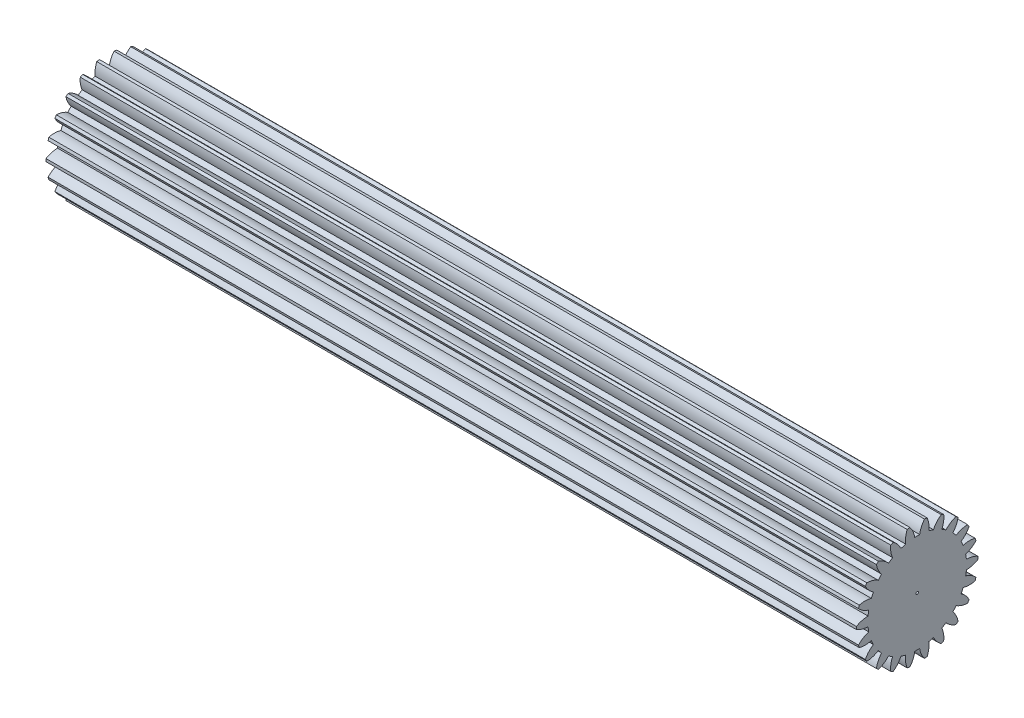
SolidWorks part; units mm, degrees
ref_plane "Plane1" through (0, 0, 0) normal (0, 0, 1) x (1, 0, 0)
ref_plane "Plane2" through (0, 0, 0) normal (0, 1, 0) x (1, 0, 0)
ref_plane "Plane3" through (0, 0, 0) normal (1, 0, 0) x (0, 0, -1)
sketch "HoldingSke" plane through (0, 0, 0) normal (0, 1, 0) x (1, 0, 0)
  line L0 (0, 0) -> (376.8075, -152.2401)
  line L1 (-15, 0) -> (100, 0) construction
  line L2 (0, 0) -> (-2.1039, 2.3779)
  line L3 (0, 0) -> (-11.863, 4.5341)
  line L4 (0, 0) -> (8.0072, 3.2351)
  line L5 (0, 0) -> (-47.5972, -17.7524)
  line L6 (0, 0) -> (-210.5566, -142.0631)
  line L7 (-2.1039, 2.3779) -> (52.5694, 250.4239)
  line L8 (-76.2, 54.61) -> (-75.184, 54.61)
  line L9 (-71.009, 38.7566) -> (-53.1078, 45.2721)
  line L10 (-76.2, 71.12) -> (104.1128, 71.12)
  line L11 (0, 0) -> (-254, 0)
  line L12 (-76.2, 101.6) -> (-76.1428, 101.6)
  line L13 (24.9733, 27.94) -> (52.9518, 28.4284)
  line L14 (24.9733, 27.94) -> (24.9746, 27.94)
  line L15 (24.9733, 27.94) -> (100.4006, 29.5858)
  circle A0 centre (0, 0) radius 0.3969
  circle A1 centre (0, 0) radius 15.4769
  circle A2 centre (0, 0) radius 38.1
  circle A3 centre (0, 0) radius 0.3969
  dimension "MHD" = 30.9537
  dimension "Hub_dia" = 76.2
  dimension "Bore" = 0.7937
  dimension "MBD" = 0.7937
  dimension "Num_teeth" = 22
  dimension "Pitch" = 406.4
  dimension "Overall_len" = 50.8
  dimension "Show_teeth" = 22
  dimension "Thickness" = 254
  dimension "OAL" = 254.0001
  dimension "T_dim" = 1.016
  dimension "Ap" = 20
  dimension "H" = 19.05
  dimension "Pitch_radius" = 180.3128
  dimension "Width" = 254
  dimension "Backlash" = 0.0571
  dimension "Addendum_fac" = 1
  dimension "Dedendum_fac" = 1.25
  dimension "Clearance_fac" = 0.25
  dimension "Dedendum_add" = 0.0013
sketch "BasProSke" plane through (0, 0, 0) normal (0, 1, 0) x (1, 0, 0)
  line L0 (-10, 0) -> (60, 0) construction
  line L1 (0, 0) -> (0, 19.05)
  line L2 (0, 0) -> (254, 0)
  line L3 (254, 0) -> (254, 19.05)
  line L4 (254, 19.05) -> (0, 19.05)
  dimension "Thickness" = 254
  dimension "Diameter" = 38.1
revolve "Base-Revolve" add sketch "BasProSke" angle 360 about L0
sketch "TooCutSke" plane through (0, 0, 0) normal (1, 0, 0) x (0, 0, -1)
  line L1 (0, 0) -> (0, 107) construction
  line L2 (0, 0) -> (-1.3457, 17.4106) construction
  line L3 (0, 0) -> (-4.9596, 34.495) construction
  line L4 (-1.3457, 17.4106) -> (-2.4798, 17.2475) construction
  arc A0 (0.7746, 15.4575) -> (-0.7746, 15.4575) centre (0, 0) ccw
  arc A1 (2.3019, 18.936) -> (-2.3019, 18.936) centre (0, 0) ccw
  circle A2 centre (0, 0) radius 17.4625 construction
  circle A3 centre (0, 0) radius 16.4094 construction
  arc A4 (-0.7746, 15.4575) -> (-2.3019, 18.936) centre (-7.6929, 14.4944) ccw
  arc A5 (2.3019, 18.936) -> (0.7746, 15.4575) centre (7.6929, 14.4944) ccw
  dimension "Root_dia" = 30.9537
  dimension "Overcut_dia" = 38.1508
  dimension "Pitch_dia" = 34.925
  dimension "Base_dia" = 32.8188
  dimension "Flank_rad" = 6.985
  dimension "Half_ang" = 8.182
  dimension "Half_CT" = 1.1457
extrude "ToothCut" cut sketch "TooCutSke" along normal through all
fillet "Breaks" [suppressed] radius 0.0318
fillet "RootFillets" [suppressed] radius 0.3981
pattern_circular "TeethCuts" count 22 every 16.364 about axis through (-10, 0, 0) along (1, 0, 0) of "ToothCut", "RootFillets", "Breaks"
sketch "HubNeaOneSke" plane through (0, 0, 0) normal (-1, 0, 0) x (0, 0, 1)
  circle A0 centre (0, 0) radius 15.4769
  dimension "Diameter" = 30.9537
extrude "HubNearOne" [suppressed] add sketch "HubNeaOneSke" along normal blind 38.1001
sketch "HubNeaBotSke" plane through (0, 0, 0) normal (-1, 0, 0) x (0, 0, 1)
  circle A0 centre (0, 0) radius 15.4769
  dimension "Diameter" = 30.9537
extrude "HubNearBoth" [suppressed] add sketch "HubNeaBotSke" along normal blind 19.05
ref_plane "FarPln" through (254, 0, 0) normal (1, 0, 0) x (0, 0, -1)
sketch "HubFarSke" plane through (254, 0, 0) normal (1, 0, 0) x (0, 0, -1)
  circle A0 centre (0, 0) radius 15.4769
  dimension "Diameter" = 30.9537
extrude "HubFar" [suppressed] add sketch "HubFarSke" along normal blind 19.05
sketch "BorSke" plane through (0, 0, 0) normal (1, 0, 0) x (0, 0, -1)
  circle A0 centre (0, 0) radius 0.3969
  dimension "Diameter" = 0.7937
extrude "Bore" cut sketch "BorSke" along normal mid plane 508.0001
sketch "KeySke" plane through (0, 0, 0) normal (1, 0, 0) x (0, 0, -1)
  line L0 (-0.127, 0) -> (-0.127, 0.6191)
  line L1 (-0.127, 0.6191) -> (0.127, 0.6191)
  line L2 (0.127, 0.6191) -> (0.127, 0)
  line L3 (0, 0) -> (0, 34) construction
  line L4 (-0.127, 0) -> (0.127, 0)
  dimension "Offset" = 0.6191
  dimension "Width" = 0.254
extrude "Keyway" [suppressed] cut sketch "KeySke" along normal mid plane 508.0001
pattern_circular "Keyway2" [suppressed] count 2 every 90 about axis through (-10, 0, 0) along (1, 0, 0)
equation "' \"Pitch@HoldingSke\" = 4"
equation "' \"Num_teeth@HoldingSke\" = 12"
equation "' \"Ap@HoldingSke\" =  20"
equation "' \"Ap@HoldingSke\" = 20"
equation "' \"Width@HoldingSke\" = 0.5"
equation "' \"Hub_dia@HoldingSke\"= 1"
equation "' \"Hub_dia@HoldingSke\" = 1"
equation "' \"Overall_len@HoldingSke\" = 1.0"
equation "' \"Bore@HoldingSke\" = 0.75"
equation "' \"T_dim@HoldingSke\" = 0.85"
equation "' \"Width@KeySke\" = 0.25"
equation "' \"Show_teeth@HoldingSke\" = 13"
equation "' \"Backlash@HoldingSke\" = 0.009"
equation "' \"Addendum_fac@HoldingSke\" = 1.0"
equation "' \"Dedendum_fac@HoldingSke\" = 1.25"
equation "' \"Dedendum_add@HoldingSke\" = 0.00005"
equation "' \"Clearance_fac@HoldingSke\" = 0.25"
equation "' \"Pitch@HoldingSke\" = 0.5"
equation "' \"Num_teeth@HoldingSke\" = 23"
equation "' \"Show_teeth@HoldingSke\" = 23"
equation "' \"Backlash@HoldingSke\" = 0.0375"
equation "\"Overcut_dia@TooCutSke\" = (\"Num_teeth@HoldingSke\" + 2 * \"Addendum_fac@HoldingSke\") / \"Pitch@HoldingSke\" + 0.002"
equation "\"Pitch_dia@TooCutSke\" = \"Num_teeth@HoldingSke\" / \"Pitch@HoldingSke\""
equation "\"Base_dia@TooCutSke\" = \"Num_teeth@HoldingSke\" / \"Pitch@HoldingSke\" * cos((\"Ap@HoldingSke\"  * 3.14159265 / 180))"
equation "\"Root_dia@TooCutSke\" = (\"Num_teeth@HoldingSke\" + 2) / \"Pitch@HoldingSke\" - 2 * (\"Addendum_fac@HoldingSke\" + \"Dedendum_fac@HoldingSke\") / \"Pitch@HoldingSke\" - \"Dedendum_add@HoldingSke\" * 2"
equation "\"Half_ang@TooCutSke\" = 180 / \"Num_teeth@HoldingSke\""
equation "\"Half_CT@TooCutSke\" = \"Num_teeth@HoldingSke\" / \"Pitch@HoldingSke\" * sin((3.14159265 / 2 / \"Num_teeth@HoldingSke\")) / 2 - 7 * \"Backlash@HoldingSke\" / 4"
equation "\"Flank_rad@TooCutSke\" = \"Num_teeth@HoldingSke\" / \"Pitch@HoldingSke\" / 5"
equation "\"Radius@RootFillets\" = \"Clearance_fac@HoldingSke\" / \"Pitch@HoldingSke\" + \"Dedendum_add@HoldingSke\""
equation "\"Break_rad@Breaks\" = 0.02 / \"Pitch@HoldingSke\""
equation "\"Thickness@HoldingSke\" = \"Width@HoldingSke\""
equation "\"OAL@HoldingSke\" = \"Thickness@HoldingSke\""
equation "\"MHD@HoldingSke\" = (\"Num_teeth@HoldingSke\" + 2) / \"Pitch@HoldingSke\" - 2 * (\"Addendum_fac@HoldingSke\" + \"Dedendum_fac@HoldingSke\")  / \"Pitch@HoldingSke\" - \"Dedendum_add@HoldingSke\" * 2"
equation "\"MBD@HoldingSke\" = (\"Num_teeth@HoldingSke\" + 2) / \"Pitch@HoldingSke\" - 2 * (\"Addendum_fac@HoldingSke\" + \"Dedendum_fac@HoldingSke\")  / \"Pitch@HoldingSke\" - \"Dedendum_add@HoldingSke\" * 2 - 0.002"
equation "\"MHD@HoldingSke\" = ((sgn( \"MHD@HoldingSke\" - \"Hub_dia@HoldingSke\" )-1)*( \"MHD@HoldingSke\" - \"Hub_dia@HoldingSke\" ))/-2+ \"Hub_dia@HoldingSke\""
equation "\"MBD@HoldingSke\" = ((sgn( \"MBD@HoldingSke\" - \"Bore@HoldingSke\" )-1)*( \"MBD@HoldingSke\" - \"Bore@HoldingSke\" ))/-2+ \"Bore@HoldingSke\""
equation "\"OAL@HoldingSke\" = ((sgn( \"OAL@HoldingSke\" - \"Overall_len@HoldingSke\" )+1)*( \"OAL@HoldingSke\" - \"Overall_len@HoldingSke\" ))/2 + \"Overall_len@HoldingSke\" + 0.000002"
equation "\"Num_teeth@TeethCuts\" = int( \"Show_teeth@HoldingSke\" ) + 1"
equation "\"Num_teeth@TeethCuts\" = ((sgn( \"Num_teeth@TeethCuts\" - \"Num_teeth@HoldingSke\" )-1)*( \"Num_teeth@TeethCuts\" - \"Num_teeth@HoldingSke\" ))/-2+ \"Num_teeth@HoldingSke\""
equation "\"Num_teeth@TeethCuts\" = ((sgn( \"Num_teeth@TeethCuts\" - 2.0)+1)*( \"Num_teeth@TeethCuts\" - 2.0))/2 +2.0"
equation "\"Angle@TeethCuts\" = 360.0 / \"Num_teeth@HoldingSke\""
equation "\"Diameter@BasProSke\" = (\"Num_teeth@HoldingSke\" + 2 * \"Addendum_fac@HoldingSke\") / \"Pitch@HoldingSke\""
equation "\"Thickness@BasProSke\"  = \"Thickness@HoldingSke\""
equation "' \"Fillet_rad@BasProSke\" =  \"Thickness@HoldingSke\" * 0.05"
equation "' \"Fillet_rad@BasProSke\" = \"Thickness@HoldingSke\" * 0.05"
equation "\"MHD@HoldingSke\" = ((sgn( \"MHD@HoldingSke\" - \"Root_dia@TooCutSke\" )-1)*( \"MHD@HoldingSke\" - \"Root_dia@TooCutSke\" ))/-2+ \"Root_dia@TooCutSke\""
equation "\"Diameter@HubNeaOneSke\" = \"MHD@HoldingSke\""
equation "\"Length@HubNearOne\" = \"OAL@HoldingSke\" - \"Thickness@BasProSke\""
equation "\"Diameter@HubNeaBotSke\" = \"MHD@HoldingSke\""
equation "\"Length@HubNearBoth\" = ( \"OAL@HoldingSke\" - \"Thickness@BasProSke\" ) / 2.0"
equation "\"Thickness@FarPln\" = \"Thickness@BasProSke\""
equation "\"Diameter@HubFarSke\" = \"MHD@HoldingSke\""
equation "\"Length@HubFar\" = ( \"OAL@HoldingSke\" - \"Thickness@BasProSke\" ) / 2.0"
equation "\"Diameter@BorSke\" = \"MBD@HoldingSke\""
equation "\"D1@Bore\" = \"OAL@HoldingSke\" * 2.0"
equation "\"D1@Keyway\" = \"OAL@HoldingSke\" * 2.0"
equation "\"Offset@KeySke\" = \"T_dim@HoldingSke\" - \"MBD@HoldingSke\" / 2.0"
